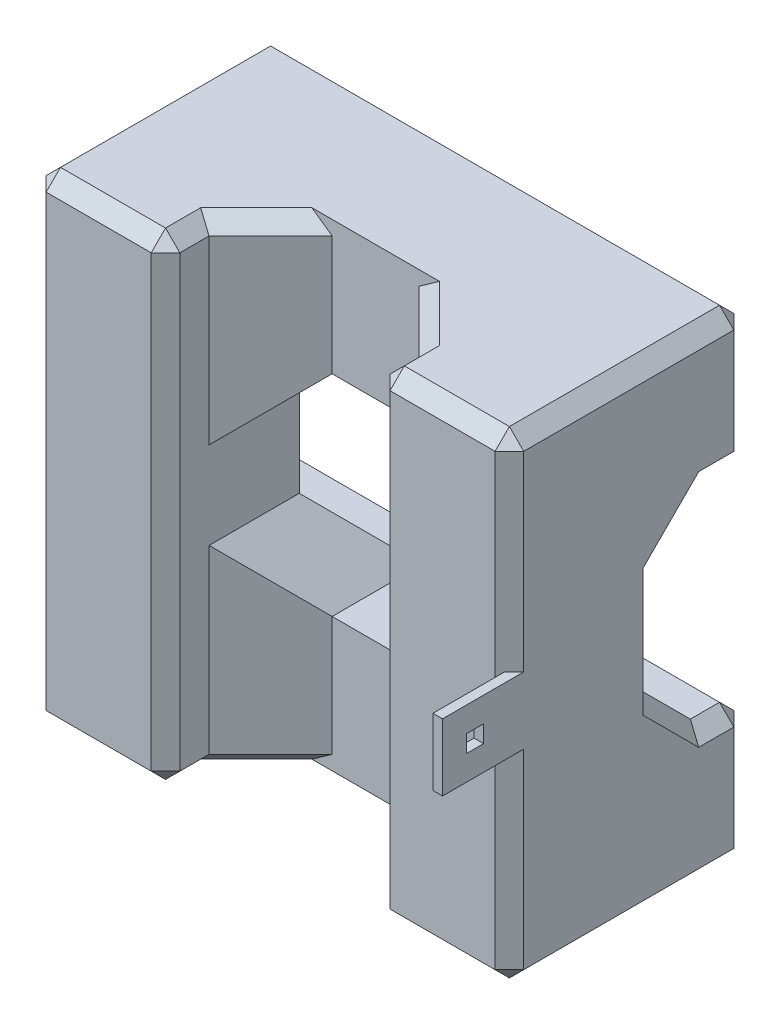
SolidWorks part; units mm, degrees
ref_plane "Front" through (0, 0, 0) normal (0, 0, 1) x (1, 0, 0)
ref_plane "Top" through (0, 0, 0) normal (0, 1, 0) x (1, 0, 0)
ref_plane "Right" through (0, 0, 0) normal (1, 0, 0) x (0, 0, -1)
sketch "Sketch1" plane through (0, 0, 0) normal (0, 0, 1) x (1, 0, 0)
  line L1 (0, 0) -> (50, 0)
  line L2 (0, 0) -> (0, 50)
  line L3 (0, 50) -> (50, 50)
  line L4 (50, 0) -> (50, 50)
  dimension "D1" = 50
extrude "Boss-Extrude1" add sketch "Sketch1" along normal blind 25
sketch "Sketch2" plane through (0, 0, 0) normal (0, -1, 0) x (1, 0, 0)
  line L0 (0, 25) -> (50, 25) construction
  line L1 (29.5563, 36) -> (20.4437, 36)
  line L2 (20.4437, 36) -> (14, 29.5563)
  line L3 (14, 29.5563) -> (14, 20.4437)
  line L4 (14, 20.4437) -> (20.4437, 14)
  line L5 (20.4437, 14) -> (29.5563, 14)
  line L6 (29.5563, 14) -> (36, 20.4437)
  line L7 (36, 20.4437) -> (36, 29.5563)
  line L8 (36, 29.5563) -> (29.5563, 36)
  circle A0 centre (25, 25) radius 11 construction
  dimension "D1" = 22
extrude "Cut-Extrude1" cut sketch "Sketch2" against normal through all
sketch "Sketch3" plane through (0, 0, 0) normal (-1, 0, 0) x (0, 0, 1)
  line L0 (0, 50) -> (0, 0) construction
  line L1 (4.5563, 14) -> (11, 20.4437)
  line L2 (11, 20.4437) -> (11, 29.5563)
  line L3 (11, 29.5563) -> (4.5563, 36)
  line L4 (4.5563, 36) -> (-4.5563, 36)
  line L5 (-4.5563, 36) -> (-11, 29.5563)
  line L6 (-11, 29.5563) -> (-11, 20.4437)
  line L7 (-11, 20.4437) -> (-4.5563, 14)
  line L8 (-4.5563, 14) -> (4.5563, 14)
  circle A0 centre (0, 25) radius 11 construction
  dimension "D1" = 22
extrude "Cut-Extrude2" cut sketch "Sketch3" against normal through all
sketch "Sketch4" plane through (0, 0, 25) normal (0, 0, 1) x (1, 0, 0)
  line L0 (20.4437, 50) -> (29.5563, 50) construction
  line L1 (29.5563, 36) -> (20.4437, 36)
  line L2 (20.4437, 36) -> (14, 29.5563)
  line L3 (14, 29.5563) -> (14, 20.4437)
  line L4 (14, 20.4437) -> (20.4437, 14)
  line L5 (20.4437, 14) -> (29.5563, 14)
  line L6 (29.5563, 14) -> (36, 20.4437)
  line L7 (36, 20.4437) -> (36, 29.5563)
  line L8 (36, 29.5563) -> (29.5563, 36)
  line L9 (25, 50) -> (25, 25) construction
  line L10 (25, 25) -> (25, 0) construction
  line L11 (20.4437, 0) -> (29.5563, 0) construction
  circle A0 centre (25, 25) radius 11 construction
extrude "Cut-Extrude3" cut sketch "Sketch4" against normal through all
chamfer "Chamfer1" distance 1.5 angle 45 36 edges at (25, 14, 0) (25, 50, 0) (0, 50, 12.5) (0, 43, 0) (0, 17.2218, 7.7782) (0, 14, 2.2782) (0, 7, 0) (0, 32.7782, 7.7782) (0, 36, 2.2782) (32.7782, 50, 17.2218) (36, 50, 22.7218) (43, 50, 25) (25, 36, 0) (50, 32.7782, 7.7782) (50, 36, 2.2782) (50, 43, 0) (50, 50, 12.5) (50, 17.2218, 7.7782) (50, 14, 2.2782) (50, 7, 0) (36, 25, 25) (50, 25, 25) (32.7782, 0, 17.2218) (36, 0, 22.7218) (43, 0, 25) (50, 0, 12.5) (25, 0, 0) (0, 0, 12.5) (7, 0, 25) (0, 25, 25) (7, 50, 25) (17.2218, 50, 17.2218) (14, 50, 22.7218) (14, 25, 25) (14, 0, 22.7218) (17.2218, 0, 17.2218)
sketch "Sketch5" plane through (0, 0, 25) normal (0, 0, 1) x (1, 0, 0)
  line L0 (50, 48.5) -> (50, 1.5) construction
  line L1 (50, 28.5) -> (49, 28.5)
  line L2 (50, 28.5) -> (50, 21.5)
  line L3 (50, 21.5) -> (49, 21.5)
  line L4 (49, 28.5) -> (49, 21.5)
  point P6 (50, 25)
  dimension "D1" = 7
  dimension "D2" = 1
extrude "Boss-Extrude2" add sketch "Sketch5" along normal blind 7 and the other way blind 10
sketch "Sketch6" plane through (50, 0, 0) normal (1, 0, 0) x (0, 0, -1)
  line L0 (-29.5, 25) -> (-32, 25) construction
  line L1 (-29.5, 25.9) -> (-27.7, 25.9)
  line L2 (-29.5, 25.9) -> (-29.5, 24.1)
  line L3 (-29.5, 24.1) -> (-27.7, 24.1)
  line L4 (-27.7, 25.9) -> (-27.7, 24.1)
  line L5 (-32, 21.5) -> (-32, 28.5) construction
  dimension "D1" = 1.8
  dimension "D2" = 2.5
extrude "Cut-Extrude5" cut sketch "Sketch6" against normal through all
